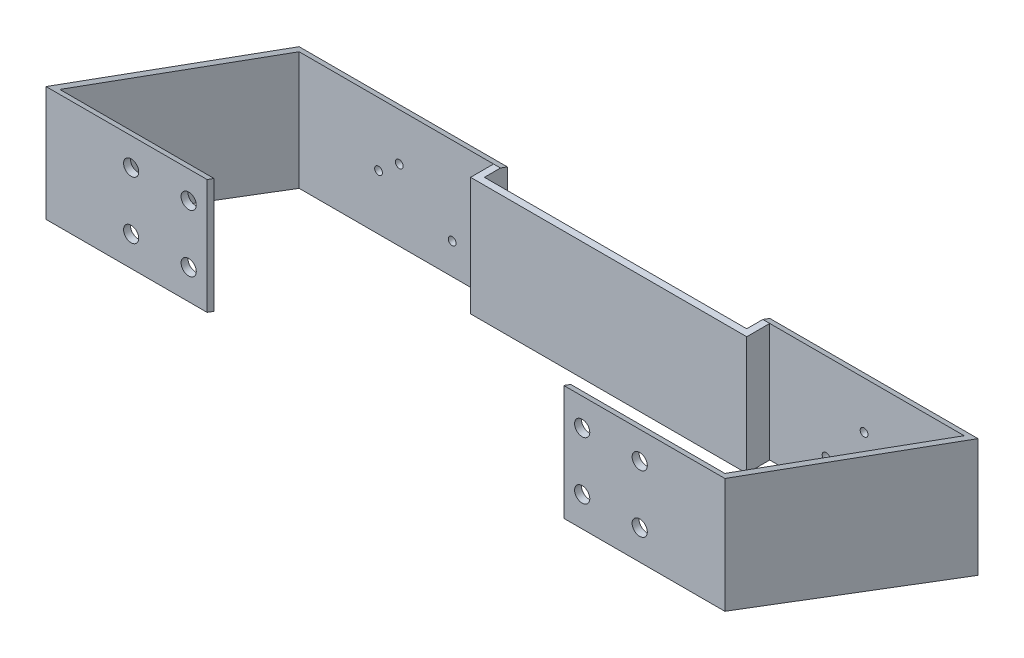
SolidWorks part; units mm, degrees
material "5052-H38"
ref_plane "Front" through (0, 0, 0) normal (0, 0, 1) x (1, 0, 0)
ref_plane "Top" through (0, 0, 0) normal (0, 1, 0) x (1, 0, 0)
ref_plane "Right" through (0, 0, 0) normal (1, 0, 0) x (0, 0, -1)
sketch "ｽｹｯﾁ1" plane through (0, 0, 0) normal (0, 0, 1) x (1, 0, 0)
  line L1 (-119.0776, 25.9902) -> (175.9224, 25.9902)
  line L2 (-119.0776, 25.9902) -> (-119.0776, -65.4598)
  line L3 (-119.0776, -65.4598) -> (175.9224, -65.4598)
  line L4 (175.9224, 25.9902) -> (175.9224, -65.4598)
  line L5 (-119.0776, 25.9902) -> (175.9224, -65.4598) construction
  line L6 (-119.0776, -65.4598) -> (175.9224, 25.9902) construction
  point P4 (28.4224, -19.7348)
  dimension "D1" = 91.45
  dimension "D2" = 295
extrude "ﾎﾞｽ - 押し出し1" add sketch "ｽｹｯﾁ1" along normal blind 3
sketch "ｽｹｯﾁ4" plane through (0, 0, 3) normal (0, 0, 1) x (1, 0, 0)
  line L0 (-119.0776, -65.4598) -> (175.9224, -65.4598) construction
  line L1 (-119.0776, 25.9902) -> (-116.0776, 25.9902)
  line L2 (-119.0776, 25.9902) -> (-119.0776, -65.4598)
  line L3 (-119.0776, -65.4598) -> (-116.0776, -65.4598)
  line L4 (-116.0776, 25.9902) -> (-116.0776, -65.4598)
  line L5 (-119.0776, 25.9902) -> (-116.0776, -65.4598) construction
  line L6 (-119.0776, -65.4598) -> (-116.0776, 25.9902) construction
  line L7 (28.4224, 38.0392) -> (28.4224, -38.1608) construction
  line L8 (175.9224, -65.4598) -> (175.9224, 25.9902) construction
  line L9 (175.9224, -65.4598) -> (172.9224, -65.4598)
  line L10 (175.9224, 25.9902) -> (172.9224, 25.9902)
  line L11 (175.9224, 25.9902) -> (175.9224, -65.4598)
  line L12 (172.9224, 25.9902) -> (172.9224, -65.4598)
  point P4 (-117.5776, -19.7348)
  dimension "D1" = 3
extrude "ﾎﾞｽ - 押し出し2" add sketch "ｽｹｯﾁ4" along normal blind 104
sketch "ｽｹｯﾁ5" plane through (0, 0, 107) normal (0, 0, 1) x (1, 0, 0)
  line L0 (-116.0776, -65.4598) -> (172.9224, -65.4598) construction
  line L1 (-119.0776, 25.9902) -> (-49.0776, 25.9902)
  line L2 (-119.0776, 25.9902) -> (-119.0776, -65.4598)
  line L3 (-119.0776, -65.4598) -> (-49.0776, -65.4598)
  line L4 (-49.0776, 25.9902) -> (-49.0776, -65.4598)
  line L5 (-119.0776, 25.9902) -> (-49.0776, -65.4598) construction
  line L6 (-119.0776, -65.4598) -> (-49.0776, 25.9902) construction
  line L7 (28.4224, 34.3478) -> (28.4224, -48.4832) construction
  line L8 (175.9224, -65.4598) -> (175.9224, 25.9902) construction
  line L9 (175.9224, 25.9902) -> (175.9224, -65.4598)
  line L10 (175.9224, 25.9902) -> (105.9224, 25.9902)
  line L11 (105.9224, 25.9902) -> (105.9224, -65.4598)
  line L12 (175.9224, -65.4598) -> (105.9224, -65.4598)
  point P4 (-84.0776, -19.7348)
  dimension "D1" = 70
extrude "ﾎﾞｽ - 押し出し3" add sketch "ｽｹｯﾁ5" along normal blind 3
sketch "ｽｹｯﾁ24" plane through (175.9224, 0, 0) normal (1, 0, 0) x (0, 0, -1)
  line L0 (0, -65.4598) -> (0, -14.0098)
  line L2 (0, -65.4598) -> (0, 25.9902) construction
  line L3 (0, -14.0098) -> (-110, 25.9902)
  line L4 (-110, 25.9902) -> (-110, -24.0098)
  line L5 (-110, -65.4598) -> (-110, 25.9902) construction
  line L6 (-110, -24.0098) -> (0, -65.4598)
  line M5 (0, -65.4598) -> (0, 25.9902)
  line M6 (0, 25.9902) -> (-110, 25.9902)
  line M7 (-110, 25.9902) -> (-110, -65.4598)
  line M8 (-110, -65.4598) -> (0, -65.4598)
  dimension "D1" = 51.45
  dimension "D2" = 50
extrude "ｶｯﾄ - 押し出し1" cut sketch "ｽｹｯﾁ24" against normal through all contours L3 M5 M6 | L6 M7 M8
hole_wizard "M6 すきま穴1" positions "ｽｹｯﾁ33" profile "ｽｹｯﾁ34" hole size "M6" standard "JIS"
sketch "ｽｹｯﾁ33" plane through (0, 0, 110) normal (0, 0, 1) x (1, 0, 0)
  line L0 (175.9224, 25.9902) -> (105.9224, 25.9902) construction
  line L2 (105.9224, 25.9902) -> (105.9224, -24.0098) construction
  line L3 (28.4224, 44.5856) -> (28.4224, -86.3438) construction
  line L5 (175.9224, -24.0098) -> (175.9224, 25.9902) construction
  line L6 (-119.0776, 25.9902) -> (-119.0776, -24.0098) construction
  point P0 (113.9224, 13.9902)
  point P19 (113.9224, -11.0098)
  point P21 (138.9224, -11.0098)
  point P23 (138.9224, 13.9902)
  point P33 (-57.0776, 13.9902)
  point P34 (-57.0776, -11.0098)
  point P35 (-82.0776, -11.0098)
  point P36 (-82.0776, 13.9902)
  dimension "D1" = 12
  dimension "D2" = 8
  dimension "D3" = 25
  dimension "D4" = 25
sketch "ｽｹｯﾁ34" plane through (113.9224, 13.9902, 110) normal (1, 0, 0) x (0, -1, 0)
  line L0 (0, 0) -> (0, 3)
  line L1 (0, 3) -> (3.3, 3)
  line L2 (3.3, 3) -> (3.3, 0)
  line L5 (3.3, 0) -> (0, 0)
  line L11 (0, -6.35) -> (0, 107.95) construction
  dimension "通し穴の直径" = 6.6
  dimension "通し穴の深さ" = 3
hole_wizard "M3 すきま穴1" positions "ｽｹｯﾁ37" profile "ｽｹｯﾁ38" hole size "M3" standard "JIS" end condition up to next
sketch "ｽｹｯﾁ37" plane through (0, 0, 3) normal (0, 0, 1) x (1, 0, 0)
  line L0 (28.4224, 10.5193) -> (28.4224, -93.1711) construction
  line L2 (-116.0776, -64.3293) -> (-116.0776, -12.9189) construction
  line L3 (172.9224, -12.9189) -> (172.9224, -64.3293) construction
  line L4 (172.9224, -12.9189) -> (-116.0776, -12.9189) construction
  point P0 (-72.5776, -33.4189)
  point P2 (-81.5776, -40.4189)
  point P4 (-49.5776, -50.9189)
  point P17 (138.4224, -40.4189)
  point P18 (129.4224, -33.4189)
  point P19 (112.9224, -50.9189)
  dimension "D1" = 101
  dimension "D2" = 110
  dimension "D3" = 32
  dimension "D4" = 25.5
  dimension "D5" = 7
  dimension "D6" = 27.5
  dimension "D7" = 10.5
sketch "ｽｹｯﾁ38" plane through (-72.5776, -33.4189, 3) normal (1, 0, 0) x (0, -1, 0)
  line L0 (0, 0) -> (0, 3)
  line L1 (0, 3) -> (1.7, 3)
  line L2 (1.7, 3) -> (1.7, 0)
  line L5 (1.7, 0) -> (0, 0)
  line L11 (0, -6.35) -> (0, 107.95) construction
  dimension "通し穴の直径" = 3.4
  dimension "通し穴の深さ" = 3
sketch "ｽｹｯﾁ39" plane through (0, 0, 3) normal (0, 0, 1) x (1, 0, 0)
  line L0 (172.9224, -12.9189) -> (-116.0776, -12.9189) construction
  line L1 (-31.5776, -12.9189) -> (-28.5776, -12.9189)
  line L2 (-31.5776, -12.9189) -> (-31.5776, -64.3293)
  line L3 (-31.5776, -64.3293) -> (-28.5776, -64.3293)
  line L4 (-28.5776, -12.9189) -> (-28.5776, -64.3293)
  line L5 (-31.5776, -12.9189) -> (-28.5776, -64.3293) construction
  line L6 (-31.5776, -64.3293) -> (-28.5776, -12.9189) construction
  line L7 (-116.0776, -64.3293) -> (172.9224, -64.3293) construction
  line L8 (28.4224, 26.4512) -> (28.4224, -84.2902) construction
  line L9 (-116.0776, -64.3293) -> (-116.0776, -12.9189) construction
  line L10 (172.9224, -12.9189) -> (172.9224, -64.3293) construction
  line L11 (88.4224, -64.3293) -> (85.4224, -64.3293)
  line L12 (88.4224, -12.9189) -> (85.4224, -12.9189)
  line L13 (88.4224, -12.9189) -> (88.4224, -64.3293)
  line L14 (85.4224, -12.9189) -> (85.4224, -64.3293)
  point P4 (-30.0776, -38.6241)
  dimension "D1" = 3
  dimension "D2" = 57
extrude "ﾎﾞｽ - 押し出し5" add sketch "ｽｹｯﾁ39" along normal blind 10
sketch "ｽｹｯﾁ42" plane through (88.4224, 0, 0) normal (1, 0, 0) x (0, 0, -1)
  line L0 (-13, -64.3293) -> (-3, -64.3293) construction
  line L1 (-13, -12.9189) -> (-10, -12.9189)
  line L2 (-13, -12.9189) -> (-13, -64.3293)
  line L3 (-13, -64.3293) -> (-10, -64.3293)
  line L4 (-10, -12.9189) -> (-10, -64.3293)
  line L5 (-13, -12.9189) -> (-10, -64.3293) construction
  line L6 (-13, -64.3293) -> (-10, -12.9189) construction
  point P4 (-11.5, -38.6241)
  dimension "D1" = 3
extrude "ﾎﾞｽ - 押し出し6" add sketch "ｽｹｯﾁ42" against normal up to surface (117 mm away) up to face at (-28.5776, -38.6241, 8)
sketch "ｽｹｯﾁ44" plane through (0, 0, 0) normal (0, 0, -1) x (-1, 0, 0)
  line L0 (119.0776, -65.4598) -> (-175.9224, -65.4598) construction
  line L1 (-85.4224, -12.9189) -> (28.5776, -12.9189)
  line L2 (-85.4224, -12.9189) -> (-85.4224, -65.4598)
  line L3 (-85.4224, -65.4598) -> (28.5776, -65.4598)
  line L4 (28.5776, -12.9189) -> (28.5776, -65.4598)
  line L5 (-85.4224, -12.9189) -> (28.5776, -65.4598) construction
  line L6 (-85.4224, -65.4598) -> (28.5776, -12.9189) construction
  line L7 (31.5776, -12.9189) -> (116.0776, -12.9189) construction
  point P4 (-28.4224, -39.1893)
extrude "ｶｯﾄ - 押し出し5" cut sketch "ｽｹｯﾁ44" against normal up to next
